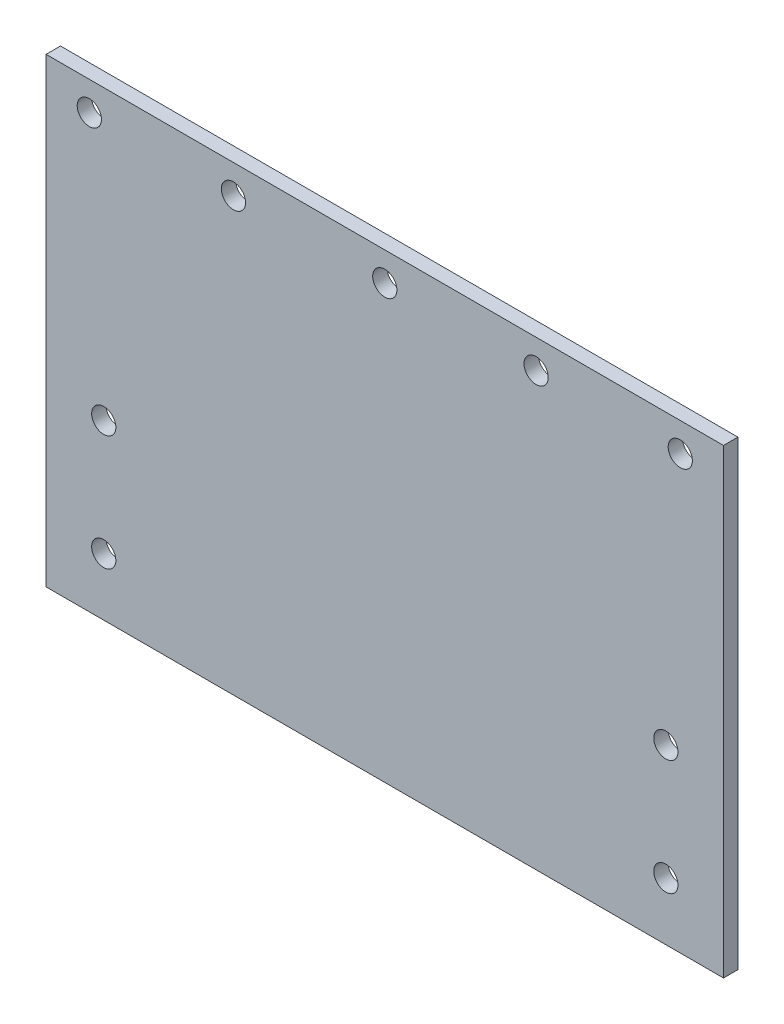
SolidWorks part; units mm, degrees
material "ABS PC"
ref_plane "Front Plane" through (0, 0, 0) normal (0, 0, 1) x (1, 0, 0)
ref_plane "Top Plane" through (0, 0, 0) normal (0, 1, 0) x (1, 0, 0)
ref_plane "Right Plane" through (0, 0, 0) normal (1, 0, 0) x (0, 0, -1)
sketch "Sketch1" plane through (0, 0, 0) normal (0, 0, 1) x (1, 0, 0)
  line L5 (117.5, -80) -> (-117.5, -80)
  line L6 (117.5, -80) -> (117.5, 80)
  line L7 (117.5, 80) -> (-117.5, 80)
  line L8 (-117.5, -80) -> (-117.5, 80)
  line L9 (117.5, -80) -> (-117.5, 80) construction
  line L10 (117.5, 80) -> (-117.5, -80) construction
  point P4 (0, 0)
  dimension "D3" = 160
  dimension "D4" = 235
extrude "Boss-Extrude1" add sketch "Sketch1" along normal blind 5
sketch "Sketch2" plane through (0, 0, 5) normal (0, 0, 1) x (1, 0, 0)
  line L0 (0, -55) -> (0, 55) construction
  line L1 (-117.5, 80) -> (-117.5, -80) construction
  line L2 (117.5, 80) -> (-117.5, 80) construction
  line L3 (-117.5, -80) -> (117.5, -80) construction
  point P0 (-102.5, 70)
  point P1 (-52.5, 70)
  point P2 (0, 70)
  point P5 (52.5, 70)
  point P6 (102.5, 70)
  point P11 (-97.5, -60)
  point P14 (-97.5, -20)
  point P17 (97.5, -20)
  point P18 (97.5, -60)
  dimension "D1" = 15
  dimension "D2" = 50
  dimension "D3" = 10
  dimension "D4" = 20
  dimension "D5" = 40
  dimension "D6" = 20
hole_wizard "M8 Clearance Hole1" positions "Sketch5" profile "Sketch7" hole size "M8" standard "GB" end condition through all
sketch "Sketch5" plane through (0, 0, 5) normal (0, 0, 1) x (1, 0, 0)
  point P0 (-102.5, 70)
  point P3 (-97.5, -20)
  point P6 (-97.5, -60)
  point P8 (-52.5, 70)
  point P11 (0, 70)
  point P14 (52.5, 70)
  point P17 (102.5, 70)
  point P20 (97.5, -20)
  point P23 (97.5, -60)
sketch "Sketch7" plane through (-102.5, 70, 5) normal (1, 0, 0) x (0, -1, 0)
  line L0 (0, 0) -> (0, 5)
  line L1 (0, 5) -> (4.2, 5)
  line L2 (4.2, 5) -> (4.2, 0)
  line L5 (4.2, 0) -> (0, 0)
  line L11 (0, -6.35) -> (0, 107.95) construction
  dimension "Thru Hole Dia." = 8.4
  dimension "Thru Hole Depth" = 5
